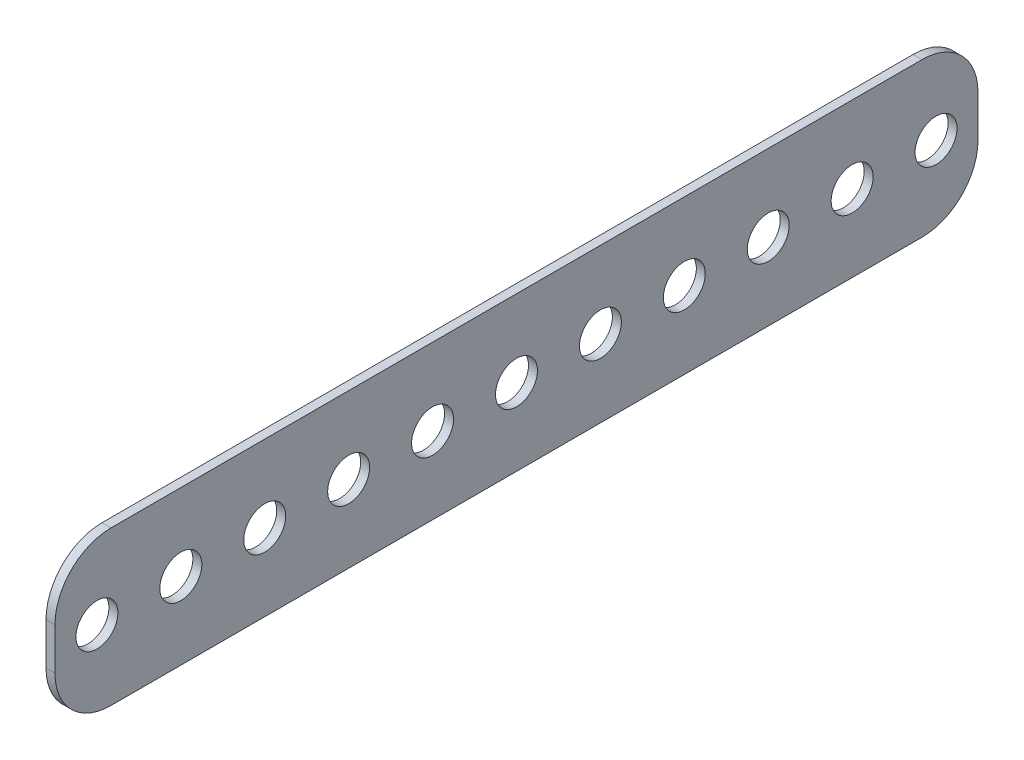
SolidWorks part; units mm, degrees
ref_plane "Front Plane" through (0, 0, 0) normal (0, 0, 1) x (1, 0, 0)
ref_plane "Top Plane" through (0, 0, 0) normal (0, 1, 0) x (1, 0, 0)
ref_plane "Right Plane" through (0, 0, 0) normal (1, 0, 0) x (0, 0, -1)
sketch "Sketch1" plane through (0, 0, 0) normal (0, 0, 1) x (1, 0, 0)
  line L1 (2.032, 0) -> (0, 0)
  line L2 (2.032, 0) -> (2.032, 34.925)
  line L3 (2.032, 34.925) -> (0, 34.925)
  line L4 (0, 0) -> (0, 34.925)
  dimension "D2" = 2.032
  dimension "D1" = 34.925
extrude "Boss-Extrude1" add sketch "Sketch1" along normal mid plane 304.8
sketch "Sketch2" plane through (0, 0, 0) normal (-1, 0, 0) x (0, 0, 1)
  line L0 (142.875, 17.4625) -> (123.825, 17.4625) construction
  line L1 (142.875, 17.4625) -> (152.4, 17.4625) construction
  line L2 (152.4, 0) -> (152.4, 34.925) construction
  circle A0 centre (142.875, 17.4625) radius 4.7625
  dimension "D1" = 9.525
  dimension "D2" = 19.05
  dimension "D3" = 9.525
extrude "Cut-Extrude1" cut sketch "Sketch2" against normal up to next
pattern_linear "LPattern1" count 16 spacing 19.05 along (0, 0, -1) of "Cut-Extrude1"
sketch "Sketch3" plane through (0, 0, 0) normal (1, 0, 0) x (0, 0, -1)
  line L0 (-152.4, 0) -> (-152.4, 34.925) construction
  point P0 (57.15, 16.9798)
  dimension "D1" = 209.55
ref_plane "Plane1" through (0, 0, -57.15) normal (0, 0, 1) x (1, 0, 0)
sketch "Sketch4" plane through (0, 0, -57.15) normal (0, 0, 1) x (1, 0, 0)
  line L4 (0, 34.925) -> (0, 0)
  line L5 (2.032, 34.925) -> (0, 34.925)
  line L6 (2.032, 0) -> (2.032, 34.925)
  line L7 (0, 0) -> (2.032, 0)
  line L8 (0, 34.925) -> (0, 0)
  line L9 (2.032, 34.925) -> (0, 34.925)
  line L10 (2.032, 0) -> (2.032, 34.925)
  line L11 (0, 0) -> (2.032, 0)
  dimension "D1" = 0
extrude "Cut-Extrude2" cut sketch "Sketch4" against normal through all
fillet "Fillet1" radius 12.7 4 edges at (1.016, 0, -57.15) (1.016, 34.925, -57.15) (1.016, 0, 152.4) (1.016, 34.925, 152.4)
equation "\"D3@Sketch2\" = \"D2@Sketch2\" / 2"
equation "\"D3@LPattern1\" = \"D2@Sketch2\""
equation "\"D1@LPattern1\" = \"D1@Boss-Extrude1\" / \"D2@Sketch2\""
